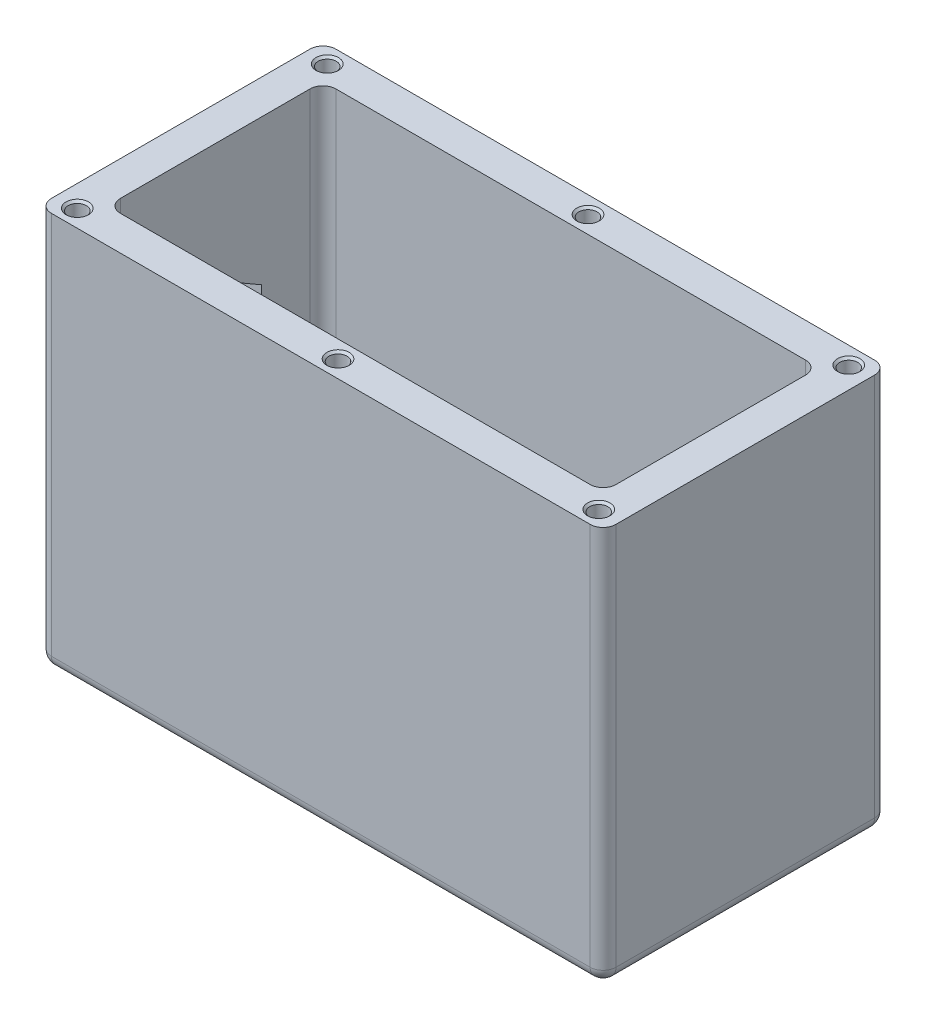
SolidWorks part; units mm, degrees
ref_plane "Front Plane" through (0, 0, 0) normal (0, 0, 1) x (1, 0, 0)
ref_plane "Top Plane" through (0, 0, 0) normal (0, 1, 0) x (1, 0, 0)
ref_plane "Right Plane" through (0, 0, 0) normal (1, 0, 0) x (0, 0, -1)
sketch "Sketch1" plane through (0, 0, 0) normal (0, 1, 0) x (1, 0, 0)
  line L1 (0, 0) -> (131, 0)
  line L2 (0, 0) -> (0, -66)
  line L3 (0, -66) -> (131, -66)
  line L4 (131, 0) -> (131, -66)
  dimension "D1" = 131
  dimension "D2" = 66
extrude "Boss-Extrude1" add sketch "Sketch1" along normal blind 92
sketch "Sketch10" plane through (0, 92, 0) normal (0, 1, 0) x (1, 0, 0)
  line L8 (8, -8) -> (8, -58)
  line L9 (8, -58) -> (123, -58)
  line L10 (123, -58) -> (123, -8)
  line L11 (123, -8) -> (8, -8)
  line L12 (8, -8) -> (8, -58)
  line L13 (8, -58) -> (123, -58)
  line L14 (123, -58) -> (123, -8)
  line L15 (123, -8) -> (8, -8)
  dimension "D1" = 8
extrude "Cut-Extrude7" cut sketch "Sketch10" against normal blind 87.5
sketch "Sketch2" plane through (0, 4.5, 0) normal (0, 1, 0) x (1, 0, 0)
  line L0 (111, -19) -> (111, -47) construction
  line L1 (123, -58) -> (123, -8) construction
  line L2 (123, -58) -> (123, -8) construction
  circle A0 centre (71, -19) radius 2.25
  circle A1 centre (111, -19) radius 2.25
  circle A2 centre (71, -47) radius 2.25
  circle A3 centre (111, -47) radius 2.25
  point P12 (123, -33)
  point P13 (111, -33)
  dimension "D1" = 4.5
  dimension "D4" = 12
  dimension "D2" = 28
  dimension "D3" = 40
extrude "Cut-Extrude1" cut sketch "Sketch2" against normal through all
sketch "Sketch3" plane through (0, 4.5, 0) normal (0, 1, 0) x (1, 0, 0)
  line L0 (111, -19) -> (111, -47) construction
  circle A0 centre (99.54, -33) radius 5
  point P6 (111, -33)
  dimension "D1" = 10
  dimension "D2" = 11.46
extrude "Cut-Extrude2" cut sketch "Sketch3" against normal through all
sketch "Sketch6" plane through (0, 92, 0) normal (0, 1, 0) x (1, 0, 0)
  line L0 (131, -66) -> (131, 0) construction
  line L1 (0, -66) -> (131, -66) construction
  line L2 (131, 0) -> (0, 0) construction
  line L3 (0, 0) -> (0, -66) construction
  line L4 (126, -62) -> (5, -62) construction
  line L5 (0, -66) -> (131, -66) construction
  circle A0 centre (126, -62) radius 2.1
  circle A1 centre (5, -62) radius 2.1
  circle A4 centre (5, -4) radius 2.1
  circle A6 centre (126, -4) radius 2.1
  circle A7 centre (65.5, -4) radius 2.1
  circle A8 centre (65.5, -62) radius 2.1
  point P14 (65.5, -66)
  point P15 (65.5, -5)
  point P16 (0, 0)
  point P17 (0, 0)
  dimension "D3" = 4.2
  dimension "D1" = 5
  dimension "D2" = 4
  dimension "D4" = 4
  dimension "D5" = 5
extrude "Cut-Extrude5" cut sketch "Sketch6" against normal blind 7.4
sketch "Sketch7" plane through (0, 4.5, 0) normal (0, 1, 0) x (1, 0, 0)
  circle A1 centre (99.54, -33) radius 5 construction
  circle A3 centre (99.54, -33) radius 8.25
  circle A6 centre (99.54, -33) radius 5
  dimension "D1" = 16.5
sketch "Sketch17" plane through (0, 0, 85) normal (1, 0, 0) x (0, 0, -1)
  line L2 (19, 92) -> (85, 92) construction
  circle A0 centre (52, 52) radius 8
  point P4 (52, 92)
  dimension "D1" = 16
  dimension "D2" = 40
extrude "Cut-Extrude9" cut sketch "Sketch17" along normal up to next
sketch "Sketch19" plane through (0, 84.6, 0) normal (0, 1, 0) x (1, 0, 0)
  circle A0 centre (5, -4) radius 1.5
  circle A2 centre (126, -4) radius 1.5
  circle A4 centre (126, -62) radius 1.5
  circle A6 centre (5, -62) radius 1.5
  circle A7 centre (65.5, -4) radius 1.5
  circle A8 centre (65.5, -62) radius 1.5
  dimension "D1" = 3
extrude "Cut-Extrude12" cut sketch "Sketch19" against normal blind 20
sketch "Sketch23" plane through (8, 0, 0) normal (1, 0, 0) x (0, 0, -1)
  line L1 (-22.2, 58.2354) -> (-33, 64.4708)
  line L2 (-33, 64.4708) -> (-43.8, 58.2354)
  line L3 (-43.8, 58.2354) -> (-43.8, 45.7646)
  line L4 (-43.8, 45.7646) -> (-33, 39.5292)
  line L5 (-33, 39.5292) -> (-22.2, 45.7646)
  line L6 (-22.2, 45.7646) -> (-22.2, 58.2354)
  circle A0 centre (-33, 52) radius 10.8 construction
  dimension "D1" = 21.6
extrude "Cut-Extrude13" cut sketch "Sketch23" against normal blind 7
hole_wizard "CSK for ST2.2 Cross recessed CTSK head tapping screws1" [suppressed] positions "Sketch21" profile "Sketch22" countersink size "ST2.2" standard "GB"
sketch "Sketch21" [suppressed] plane through (0, 0, 0) normal (0, 0, 1) x (1, 0, 0)
  point P0 (34.5, 75.5)
  point P3 (34.5, 48.5)
  point P6 (75.5, 48.5)
  point P9 (75.5, 75.5)
sketch "Sketch22" plane through (34.5, 75.5, 0) normal (1, 0, 0) x (0, 1, 0)
  line L0 (0, 0) -> (0, 12)
  line L1 (0, 12) -> (1.2, 12)
  line L2 (1.2, 12) -> (1.2, 1)
  line L3 (1.2, 1) -> (2.2, 0)
  line L5 (2.2, 0) -> (0, 0)
  line L6 (-1.2, 1) -> (-2.2, 0) construction
  line L11 (0, -6.35) -> (0, 107.95) construction
  dimension "Thru Hole Dia." = 2.4
  dimension "Thru Hole Depth" = 12
  dimension "Near C'Sink Dia." = 4.4
  dimension "Near C'Sink Angle" = 90
extrude "Cut-Extrude14" cut sketch "Sketch7" against normal blind 4.5
sketch "Sketch24" plane through (0, 4.5, 0) normal (0, 1, 0) x (1, 0, 0)
  circle A18 centre (71, -19) radius 3.25
  circle A19 centre (111, -19) radius 3.25
  circle A20 centre (71, -47) radius 3.25
  circle A21 centre (111, -47) radius 3.25
  dimension "D1" = 6.5
extrude "Cut-Extrude15" cut sketch "Sketch24" against normal blind 2
fillet "Fillet1" radius 3 16 edges at (123, 4.5, 33) (65.5, 0, 0) (65.5, 0, 66) (0, 0, 33) (8, 48.25, 58) (131, 46, 66) (0, 46, 0) (131, 46, 0) (131, 0, 33) (0, 46, 66) (123, 48.25, 58) (65.5, 4.5, 58) (8, 4.5, 33) (8, 48.25, 8) (123, 48.25, 8) (65.5, 4.5, 8)
sketch "Sketch25" plane through (0, 92, 0) normal (0, 1, 0) x (1, 0, 0)
  line L37 (123, -11) -> (123, -55) construction
  line L38 (120, -58) -> (11, -58) construction
  line L39 (11, -8) -> (120, -8) construction
  line L40 (8, -55) -> (8, -11) construction
  line L41 (126, -55) -> (126, -11)
  line L42 (120, -5) -> (11, -5)
  line L43 (11, -61) -> (120, -61)
  line L44 (5, -11) -> (5, -55)
  line L45 (126, -55) -> (126, -11)
  line L46 (120, -5) -> (11, -5)
  line L47 (11, -61) -> (120, -61)
  line L48 (5, -11) -> (5, -55)
  line L49 (123, -11) -> (123, -55)
  line L50 (120, -58) -> (11, -58)
  line L51 (11, -8) -> (120, -8)
  line L52 (8, -55) -> (8, -11)
  arc A29 (123, -11) -> (120, -8) centre (120, -11) ccw construction
  arc A30 (120, -58) -> (123, -55) centre (120, -55) ccw construction
  arc A31 (8, -55) -> (11, -58) centre (11, -55) ccw construction
  arc A32 (11, -8) -> (8, -11) centre (11, -11) ccw construction
  arc A33 (120, -61) -> (126, -55) centre (120, -55) ccw
  arc A34 (126, -11) -> (120, -5) centre (120, -11) ccw
  arc A35 (5, -55) -> (11, -61) centre (11, -55) ccw
  arc A36 (11, -5) -> (5, -11) centre (11, -11) ccw
  arc A37 (120, -61) -> (126, -55) centre (120, -55) ccw
  arc A38 (126, -11) -> (120, -5) centre (120, -11) ccw
  arc A39 (5, -55) -> (11, -61) centre (11, -55) ccw
  arc A40 (11, -5) -> (5, -11) centre (11, -11) ccw
  arc A41 (123, -11) -> (120, -8) centre (120, -11) ccw
  arc A42 (120, -58) -> (123, -55) centre (120, -55) ccw
  arc A43 (8, -55) -> (11, -58) centre (11, -55) ccw
  arc A44 (11, -8) -> (8, -11) centre (11, -11) ccw
  dimension "D1" = 3
extrude "Boss-Extrude2" [suppressed] add sketch "Sketch25" along normal blind 3
fillet "Fillet2" [suppressed] radius 0.5
chamfer "Chamfer1" distance 0.5 angle 45 6 edges at (5, 92, 64.1) (126, 92, 64.1) (126, 92, 6.1) (5, 92, 6.1) (65.5, 92, 64.1) (65.5, 92, 6.1)
